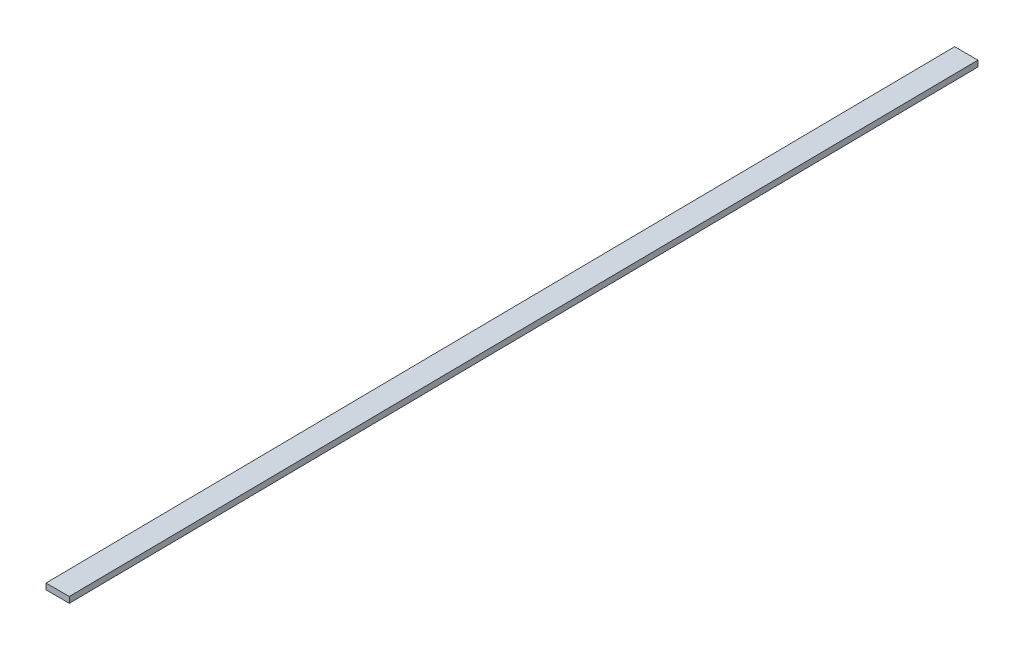
SolidWorks part; units mm, degrees
material "Spruce"
ref_plane "Front Plane" through (0, 0, 0) normal (0, 0, 1) x (1, 0, 0)
ref_plane "Top Plane" through (0, 0, 0) normal (0, 1, 0) x (1, 0, 0)
ref_plane "Right Plane" through (0, 0, 0) normal (1, 0, 0) x (0, 0, -1)
sketch "Sketch1" plane through (0, 370.5474, 4.1474) normal (0, -0.9999, -0.0112) x (1, 0, 0)
  line L0 (238.5315, 775.9505) -> (238.5521, 1493.5455)
  line L1 (257.0941, 1493.545) -> (257.0735, 775.95)
  line L4 (257.0735, 775.95) -> (238.5315, 775.9505)
  line L5 (238.5315, 775.9505) -> (238.5314, 772.7753)
  line L6 (238.5314, 772.7753) -> (257.0734, 772.7748)
  line L7 (257.0734, 772.7748) -> (257.0735, 775.95)
  line L9 (238.5315, 775.9505) -> (238.5314, 772.7753)
  line L10 (238.5314, 772.7753) -> (257.0734, 772.7748)
  line L11 (257.0734, 772.7748) -> (257.0735, 775.95)
  line L12 (238.5521, 1493.5455) -> (257.0941, 1493.545)
  line L13 (257.0941, 1493.545) -> (257.0942, 1496.7202)
  line L14 (257.0942, 1496.7202) -> (238.5522, 1496.7207)
  line L15 (238.5522, 1496.7207) -> (238.5521, 1493.5455)
  line L17 (257.0941, 1493.545) -> (257.0942, 1496.7202)
  line L18 (257.0942, 1496.7202) -> (238.5522, 1496.7207)
  line L19 (238.5522, 1496.7207) -> (238.5521, 1493.5455)
  dimension "D1" = 0
  dimension "D2" = 0
extrude "Boss-Extrude1" add sketch "Sketch1" along normal blind 4.7625
